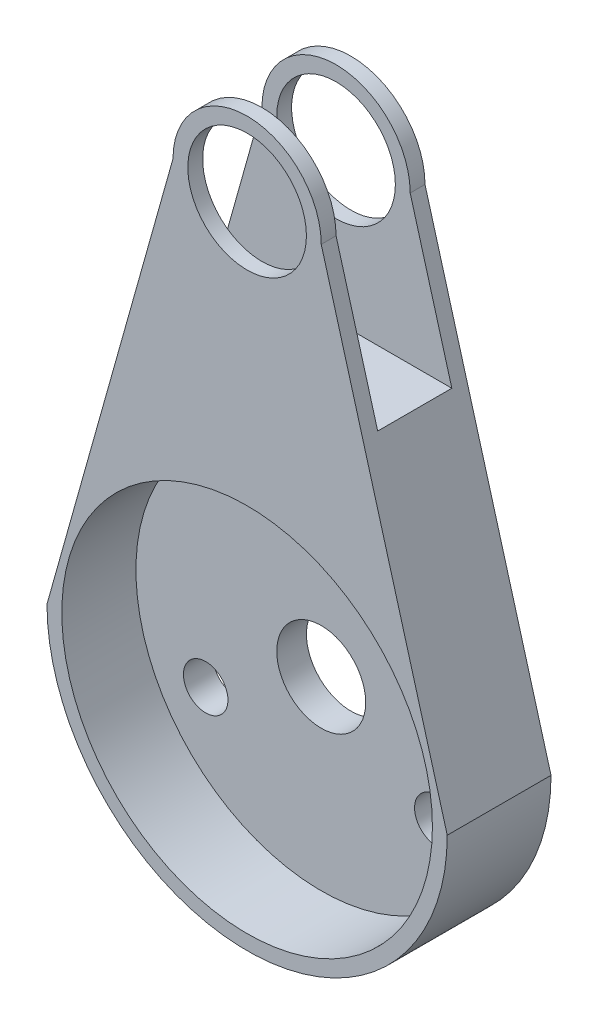
SolidWorks part; units mm, degrees
ref_plane "Plan de face" through (0, 0, 0) normal (0, 0, 1) x (1, 0, 0)
ref_plane "Plan de dessus" through (0, 0, 0) normal (0, 1, 0) x (1, 0, 0)
ref_plane "Plan de droite" through (0, 0, 0) normal (1, 0, 0) x (0, 0, -1)
sketch "Esquisse1" plane through (0, 0, 0) normal (0, 0, 1) x (1, 0, 0)
  line L0 (-16.3093, 0) -> (24.5372, 0) construction
  line L1 (5, 0) -> (13.5, -30.2655)
  line L2 (-5, 0) -> (-13.5, -30.2655)
  line L3 (-13.5, -30.2655) -> (13.5, -30.2655) construction
  line L4 (0, 0) -> (0, -30.2655) construction
  arc A0 (-5, 0) -> (5, 0) centre (0, 0) cw
  arc A1 (-13.5, -30.2655) -> (13.5, -30.2655) centre (0, -30.2655) ccw
  dimension "D1" = 5
  dimension "D2" = 13.5
  dimension "D3" = 30.2655
extrude "Boss.-Extru.1" add sketch "Esquisse1" along normal blind 7
sketch "Esquisse2" plane through (0, 0, 7) normal (0, 0, 1) x (1, 0, 0)
  line L0 (0, 0) -> (0, -43.7655) construction
  line L1 (13.5, -30.2655) -> (-13.5, -30.2655) construction
  circle A0 centre (0, -30.2655) radius 3
  arc A1 (-13.5, -30.2655) -> (13.5, -30.2655) centre (0, -30.2655) ccw construction
  dimension "D1" = 6
extrude "Enlèv. mat.-Extru.1" cut sketch "Esquisse2" against normal blind 7
sketch "Esquisse3" plane through (0, 0, 7) normal (0, 0, 1) x (1, 0, 0)
  line L0 (0, -30.2655) -> (0, 0) construction
  line L1 (0, -30.2655) -> (-7.7942, -34.7655) construction
  line L2 (0, -30.2655) -> (7.7942, -34.7655) construction
  circle A0 centre (0, -21.2655) radius 1.5
  circle A1 centre (-7.7942, -34.7655) radius 1.5
  circle A2 centre (7.7942, -34.7655) radius 1.5
  dimension "D1" = 3
  dimension "D2" = 3
  dimension "D3" = 3
  dimension "D4" = 9
  dimension "D5" = 9
  dimension "D6" = 9
  dimension "D7" = 120
  dimension "D8" = 120
extrude "Enlèv. mat.-Extru.2" cut sketch "Esquisse3" against normal blind 7
sketch "Esquisse4" plane through (0, 0, 7) normal (0, 0, 1) x (1, 0, 0)
  circle A0 centre (0, 0) radius 4
  dimension "D1" = 8
extrude "Enlèv. mat.-Extru.3" cut sketch "Esquisse4" against normal blind 7
sketch "Esquisse5" plane through (0, 0, 7) normal (0, 0, 1) x (1, 0, 0)
  circle A0 centre (0, -30.2655) radius 12.5
  dimension "D1" = 25
extrude "Enlèv. mat.-Extru.4" cut sketch "Esquisse5" against normal blind 5
ref_plane "Plan1" through (0, 10, 0) normal (0, 1, 0) x (1, 0, 0)
sketch "Esquisse6" plane through (0, 10, 0) normal (0, 1, 0) x (1, 0, 0)
  line L0 (-13.5, -7) -> (-13.5, 0) construction
  line L1 (-13.5, -1) -> (13.5, -1)
  line L2 (-13.5, -1) -> (-13.5, -6)
  line L3 (-13.5, -6) -> (13.5, -6)
  line L4 (13.5, -1) -> (13.5, -6)
  line L5 (13.5, -7) -> (13.5, 0) construction
  line L6 (13.5, 0) -> (13.5, -7) construction
  point P12 (13.5, -3.5)
  point P13 (13.5, -3.5)
  dimension "D1" = 5
extrude "Enlèv. mat.-Extru.5" cut sketch "Esquisse6" against normal blind 20
